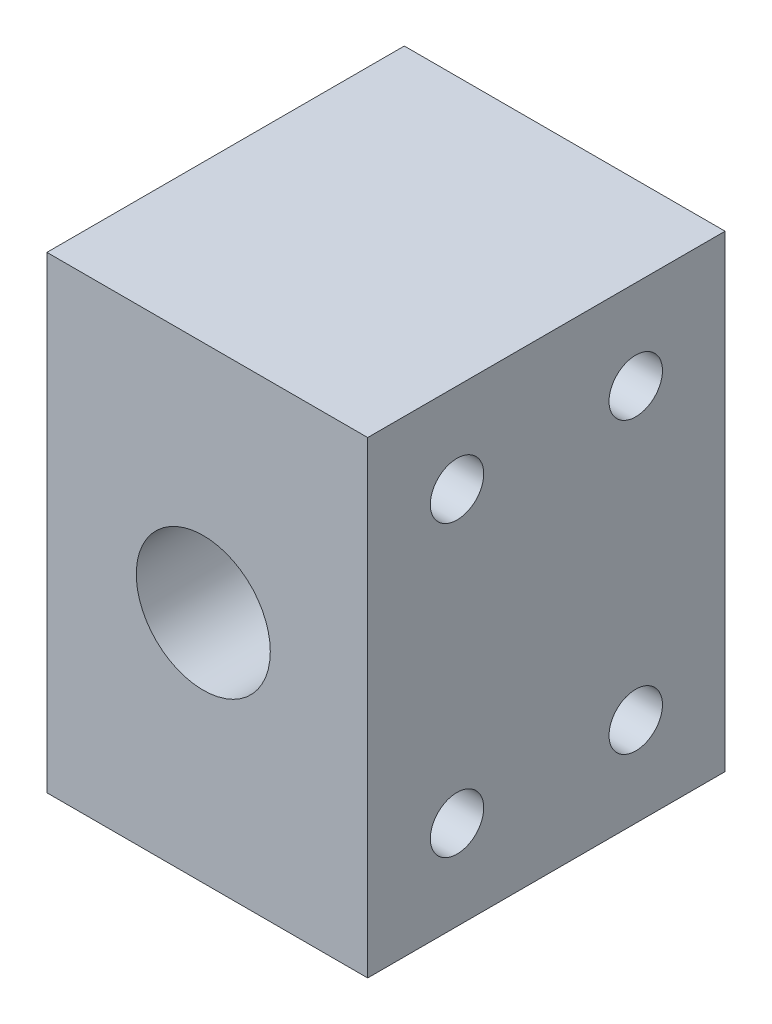
SolidWorks part; units mm, degrees
material "6061-T6 (SS)"
ref_plane "Front Plane" through (0, 0, 0) normal (0, 0, 1) x (1, 0, 0)
ref_plane "Top Plane" through (0, 0, 0) normal (0, 1, 0) x (1, 0, 0)
ref_plane "Right Plane" through (0, 0, 0) normal (1, 0, 0) x (0, 0, -1)
sketch "Sketch1" plane through (0, 0, 0) normal (0, 0, 1) x (1, 0, 0)
  line L0 (11.1125, 33.2638) -> (11.1125, 0) construction
  line L1 (0, 0) -> (22.7965, 0)
  line L2 (0, 0) -> (0, 33.2638)
  line L3 (0, 33.2638) -> (22.7965, 33.2638)
  line L4 (22.7965, 0) -> (22.7965, 33.2638)
  line L5 (0, 16.6319) -> (22.7965, 16.6319) construction
  circle A0 centre (11.1125, 16.6319) radius 4.7625
  dimension "D3" = 9.525
  dimension "D1" = 11.684
  dimension "D2" = 6.35
  dimension "D4" = 16.6319
extrude "Boss-Extrude1" add sketch "Sketch1" along normal blind 25.4
hole_wizard "set screw #10-24 Tapped Hole1" positions "Sketch6" profile "Sketch5" tap size "#10-24" standard "ANSI Inch"
sketch "Sketch6" plane through (0, 0, 0) normal (-1, 0, 0) x (0, 0, 1)
  line L0 (12.7, 33.2638) -> (12.7, 0) construction
  line L1 (25.4, 33.2638) -> (0, 33.2638) construction
  line L2 (25.4, 0) -> (0, 0) construction
  line L3 (0, 16.6319) -> (25.4, 16.6319) construction
  line L4 (0, 33.2638) -> (0, 0) construction
  line L5 (25.4, 33.2638) -> (25.4, 0) construction
  point P0 (12.7, 16.6319)
sketch "Sketch5" plane through (0, 16.6319, 12.7) normal (0, 1, 0) x (0, 0, 1)
  line L0 (0, 0) -> (0, 6.35)
  line L1 (0, 6.35) -> (1.8986, 6.35)
  line L2 (1.8986, 6.35) -> (1.8986, 0)
  line L5 (1.8986, 0) -> (0, 0)
  line L11 (0, -6.35) -> (0, 107.95) construction
  dimension "Thru Tap Drill Dia." = 3.7973
  dimension "Thru Tap Drill Depth" = 6.35
cosmetic thread "Hole Thread1" parameters "D2"=4.826
hole_wizard "mount screw #10-24 Tapped Hole2" positions "Sketch8" profile "Sketch7" tap size "#10-24" standard "ANSI Inch"
sketch "Sketch8" plane through (22.7965, 0, 0) normal (1, 0, 0) x (0, 0, -1)
  line L0 (-25.4, 26.9138) -> (0, 26.9138) construction
  line L1 (-25.4, 0) -> (-25.4, 33.2638) construction
  line L2 (0, 0) -> (0, 33.2638) construction
  line L3 (-25.4, 6.35) -> (0, 6.35) construction
  line L4 (-19.05, 33.2638) -> (-19.05, 0) construction
  line L5 (-25.4, 33.2638) -> (0, 33.2638) construction
  line L6 (-25.4, 0) -> (0, 0) construction
  line L7 (-6.35, 33.2638) -> (-6.35, 0) construction
  point P0 (-19.05, 26.9138)
  point P2 (-6.35, 26.9138)
  point P4 (-19.05, 6.35)
  point P6 (-6.35, 6.35)
  dimension "D1" = 6.35
  dimension "D2" = 6.35
  dimension "D3" = 6.35
  dimension "D4" = 6.35
cosmetic thread "Hole Thread2" parameters "D1"=9.652, "D2"=4.826
cosmetic thread "Hole Thread3" parameters "D1"=9.652, "D2"=4.826
cosmetic thread "Hole Thread4" parameters "D1"=9.652, "D2"=4.826
cosmetic thread "Hole Thread5" parameters "D1"=9.652, "D2"=4.826
sketch "Sketch7" plane through (22.7965, 26.9138, 19.05) normal (0, 1, 0) x (0, 0, -1)
  line L0 (0, 0) -> (0, 14.0948)
  line L1 (0, 14.0948) -> (1.8986, 12.954)
  line L2 (1.8986, 12.954) -> (1.8986, 0)
  line L5 (1.8986, 0) -> (0, 0)
  line L10 (0, 14.0948) -> (-1.8986, 12.954) construction
  line L11 (0, -6.35) -> (0, 107.95) construction
  dimension "Tap Drill Dia." = 3.7973
  dimension "Tap Drill Depth" = 12.954
  dimension "Drill Angle" = 118
